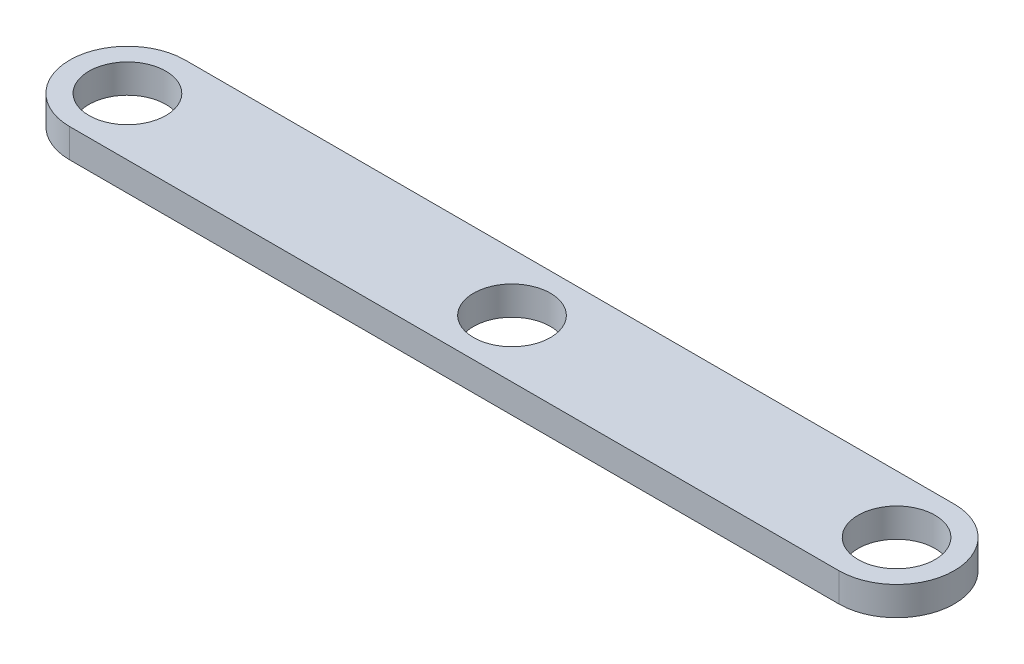
SolidWorks part; units mm, degrees
ref_plane "Front Plane" through (0, 0, 0) normal (0, 0, 1) x (1, 0, 0)
ref_plane "Top Plane" through (0, 0, 0) normal (0, 1, 0) x (1, 0, 0)
ref_plane "Right Plane" through (0, 0, 0) normal (1, 0, 0) x (0, 0, -1)
sketch "Sketch1" plane through (0, 0, 0) normal (0, 1, 0) x (1, 0, 0)
  line L0 (0, 6) -> (80, 6)
  line L1 (0, -6) -> (80, -6)
  circle A0 centre (0, 0) radius 4
  circle A1 centre (80, 0) radius 4
  arc A2 (0, 6) -> (0, -6) centre (0, 0) ccw
  arc A3 (80, -6) -> (80, 6) centre (80, 0) ccw
  circle A4 centre (0, 0) radius 6 construction
  circle A5 centre (80, 0) radius 6 construction
  dimension "D1" = 80
  dimension "D2" = 8
  dimension "D3" = 8
  dimension "D4" = 2
extrude "Boss-Extrude1" add sketch "Sketch1" along normal blind 3
sketch "Sketch2" plane through (0, 3, 0) normal (0, 1, 0) x (1, 0, 0)
  circle A0 centre (40, 0) radius 4
extrude "Cut-Extrude1" cut sketch "Sketch2" against normal through all
